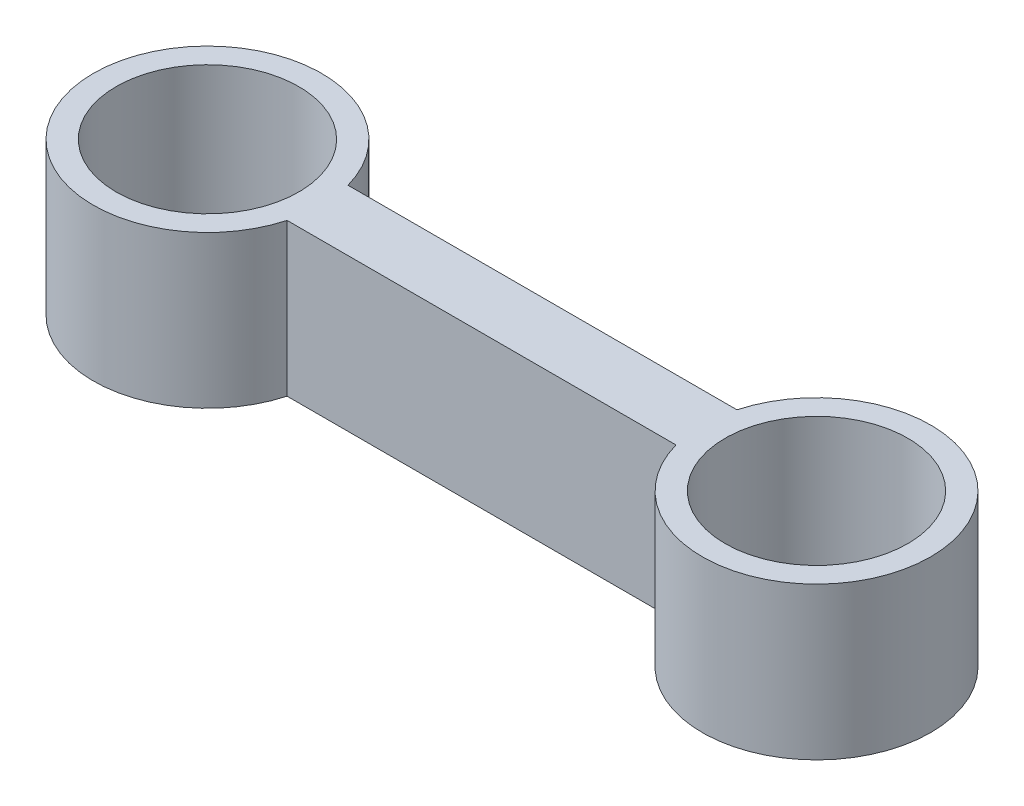
SolidWorks part; units mm, degrees
ref_plane "前视基准面" through (0, 0, 0) normal (0, 0, 1) x (1, 0, 0)
ref_plane "上视基准面" through (0, 0, 0) normal (0, 1, 0) x (1, 0, 0)
ref_plane "右视基准面" through (0, 0, 0) normal (1, 0, 0) x (0, 0, -1)
sketch "草图1" plane through (0, 0, 0) normal (0, 1, 0) x (1, 0, 0)
  line L0 (0, -5.9315) -> (0, 5.9315) construction
  line L1 (-2, 0) -> (2, 0) construction
  line L2 (-1.2772, 0.2) -> (1.2772, 0.2)
  line L3 (-1.2772, -0.2) -> (1.2772, -0.2)
  circle A0 centre (2, 0) radius 0.6
  circle A1 centre (2, 0) radius 0.75
  circle A2 centre (-2, 0) radius 0.75
  circle A3 centre (-2, 0) radius 0.6
  point P12 (0, 0)
  point P15 (0, -0.2)
  point P16 (0, 0.2)
  dimension "D1" = 1.5
  dimension "D2" = 1.2
  dimension "D3" = 4
  dimension "D4" = 0.4
extrude "凸台-拉伸1" add sketch "草图1" along normal mid plane 1 contours L2 A2 L3 A1 | A1 A0 | A2 A3
